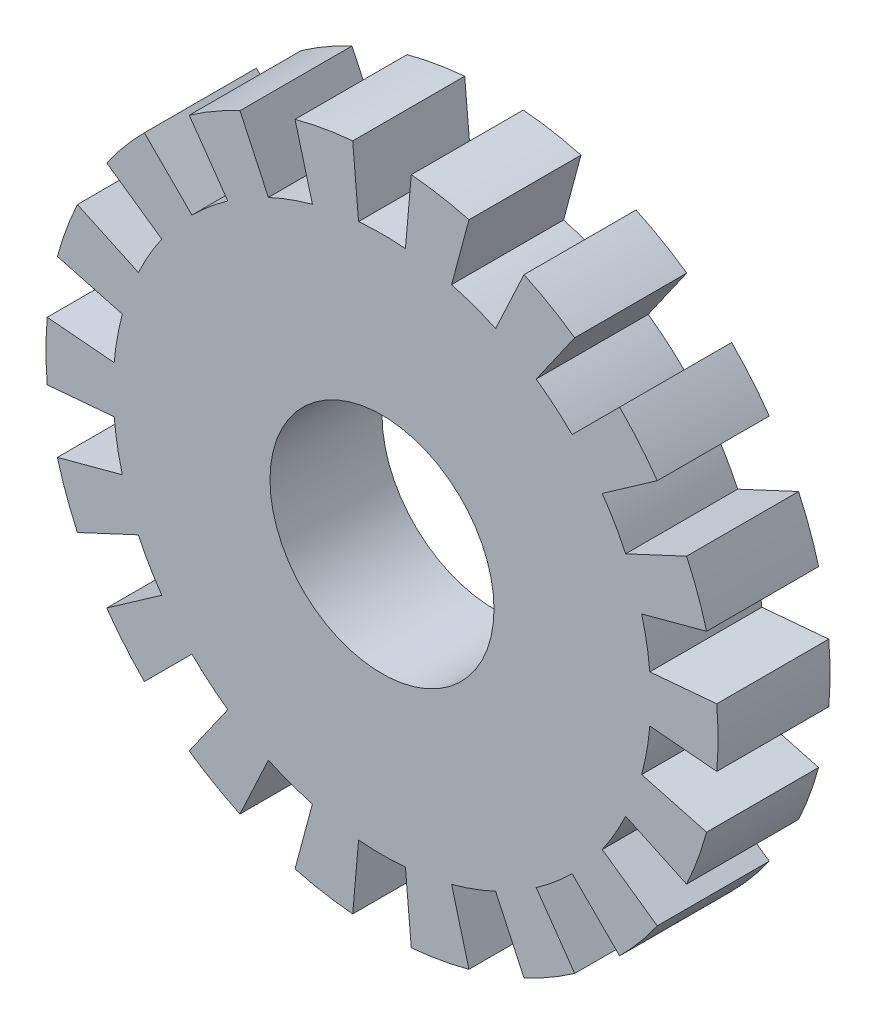
SolidWorks part; units mm, degrees
ref_plane "正面" through (0, 0, 0) normal (0, 0, 1) x (1, 0, 0)
ref_plane "平面" through (0, 0, 0) normal (0, 1, 0) x (1, 0, 0)
ref_plane "右側面" through (0, 0, 0) normal (1, 0, 0) x (0, 0, -1)
sketch "ｽｹｯﾁ1" plane through (0, 0, 0) normal (0, 0, 1) x (1, 0, 0)
  circle A0 centre (0, 0) radius 15
  dimension "D1" = 30
extrude "ﾎﾞｽ - 押し出し1" add sketch "ｽｹｯﾁ1" along normal blind 5
sketch "ｽｹｯﾁ2" plane through (0, 0, 0) normal (0, 0, -1) x (-1, 0, 0)
  line L0 (0, 0) -> (0, 15) construction
  line L1 (0, 0) -> (1.0459, 11.9543) construction
  line L2 (1.0459, 11.9543) -> (1.3073, 14.9429)
  line L3 (0, 12) -> (0, 15)
  line L4 (-1.0459, 11.9543) -> (-1.3073, 14.9429)
  line L5 (5.0714, 10.8757) -> (6.3393, 13.5946)
  line L6 (3.1058, 11.5911) -> (3.8823, 14.4889)
  line L7 (8.4853, 8.4853) -> (10.6066, 10.6066)
  line L8 (6.8829, 9.8298) -> (8.6036, 12.2873)
  line L9 (10.8757, 5.0714) -> (13.5946, 6.3393)
  line L10 (9.8298, 6.8829) -> (12.2873, 8.6036)
  line L11 (11.9543, 1.0459) -> (14.9429, 1.3073)
  line L12 (11.5911, 3.1058) -> (14.4889, 3.8823)
  line L13 (11.5911, -3.1058) -> (14.4889, -3.8823)
  line L14 (11.9543, -1.0459) -> (14.9429, -1.3073)
  line L15 (9.8298, -6.8829) -> (12.2873, -8.6036)
  line L16 (10.8757, -5.0714) -> (13.5946, -6.3393)
  line L17 (6.8829, -9.8298) -> (8.6036, -12.2873)
  line L18 (8.4853, -8.4853) -> (10.6066, -10.6066)
  line L19 (3.1058, -11.5911) -> (3.8823, -14.4889)
  line L20 (5.0714, -10.8757) -> (6.3393, -13.5946)
  line L21 (-1.0459, -11.9543) -> (-1.3073, -14.9429)
  line L22 (1.0459, -11.9543) -> (1.3073, -14.9429)
  line L23 (-5.0714, -10.8757) -> (-6.3393, -13.5946)
  line L24 (-3.1058, -11.5911) -> (-3.8823, -14.4889)
  line L25 (-8.4853, -8.4853) -> (-10.6066, -10.6066)
  line L26 (-6.8829, -9.8298) -> (-8.6036, -12.2873)
  line L27 (-10.8757, -5.0714) -> (-13.5946, -6.3393)
  line L28 (-9.8298, -6.8829) -> (-12.2873, -8.6036)
  line L29 (-11.9543, -1.0459) -> (-14.9429, -1.3073)
  line L30 (-11.5911, -3.1058) -> (-14.4889, -3.8823)
  line L31 (-11.5911, 3.1058) -> (-14.4889, 3.8823)
  line L32 (-11.9543, 1.0459) -> (-14.9429, 1.3073)
  line L33 (-9.8298, 6.8829) -> (-12.2873, 8.6036)
  line L34 (-10.8757, 5.0714) -> (-13.5946, 6.3393)
  line L35 (-6.8829, 9.8298) -> (-8.6036, 12.2873)
  line L36 (-8.4853, 8.4853) -> (-10.6066, 10.6066)
  line L37 (-3.1058, 11.5911) -> (-3.8823, 14.4889)
  line L38 (-5.0714, 10.8757) -> (-6.3393, 13.5946)
  circle A0 centre (0, 0) radius 15 construction
  arc A1 (1.0459, 11.9543) -> (-1.0459, 11.9543) centre (0, 0) ccw
  arc A2 (-1.3073, 14.9429) -> (1.3073, 14.9429) centre (0, 0) cw
  arc A3 (3.8823, 14.4889) -> (6.3393, 13.5946) centre (0, 0) cw
  arc A4 (5.0714, 10.8757) -> (3.1058, 11.5911) centre (0, 0) ccw
  arc A5 (8.6036, 12.2873) -> (10.6066, 10.6066) centre (0, 0) cw
  arc A6 (8.4853, 8.4853) -> (6.8829, 9.8298) centre (0, 0) ccw
  arc A7 (12.2873, 8.6036) -> (13.5946, 6.3393) centre (0, 0) cw
  arc A8 (10.8757, 5.0714) -> (9.8298, 6.8829) centre (0, 0) ccw
  arc A9 (14.4889, 3.8823) -> (14.9429, 1.3073) centre (0, 0) cw
  arc A10 (11.9543, 1.0459) -> (11.5911, 3.1058) centre (0, 0) ccw
  arc A11 (14.9429, -1.3073) -> (14.4889, -3.8823) centre (0, 0) cw
  arc A12 (11.5911, -3.1058) -> (11.9543, -1.0459) centre (0, 0) ccw
  arc A13 (13.5946, -6.3393) -> (12.2873, -8.6036) centre (0, 0) cw
  arc A14 (9.8298, -6.8829) -> (10.8757, -5.0714) centre (0, 0) ccw
  arc A15 (10.6066, -10.6066) -> (8.6036, -12.2873) centre (0, 0) cw
  arc A16 (6.8829, -9.8298) -> (8.4853, -8.4853) centre (0, 0) ccw
  arc A17 (6.3393, -13.5946) -> (3.8823, -14.4889) centre (0, 0) cw
  arc A18 (3.1058, -11.5911) -> (5.0714, -10.8757) centre (0, 0) ccw
  arc A19 (1.3073, -14.9429) -> (-1.3073, -14.9429) centre (0, 0) cw
  arc A20 (-1.0459, -11.9543) -> (1.0459, -11.9543) centre (0, 0) ccw
  arc A21 (-3.8823, -14.4889) -> (-6.3393, -13.5946) centre (0, 0) cw
  arc A22 (-5.0714, -10.8757) -> (-3.1058, -11.5911) centre (0, 0) ccw
  arc A23 (-8.6036, -12.2873) -> (-10.6066, -10.6066) centre (0, 0) cw
  arc A24 (-8.4853, -8.4853) -> (-6.8829, -9.8298) centre (0, 0) ccw
  arc A25 (-12.2873, -8.6036) -> (-13.5946, -6.3393) centre (0, 0) cw
  arc A26 (-10.8757, -5.0714) -> (-9.8298, -6.8829) centre (0, 0) ccw
  arc A27 (-14.4889, -3.8823) -> (-14.9429, -1.3073) centre (0, 0) cw
  arc A28 (-11.9543, -1.0459) -> (-11.5911, -3.1058) centre (0, 0) ccw
  arc A29 (-14.9429, 1.3073) -> (-14.4889, 3.8823) centre (0, 0) cw
  arc A30 (-11.5911, 3.1058) -> (-11.9543, 1.0459) centre (0, 0) ccw
  arc A31 (-13.5946, 6.3393) -> (-12.2873, 8.6036) centre (0, 0) cw
  arc A32 (-9.8298, 6.8829) -> (-10.8757, 5.0714) centre (0, 0) ccw
  arc A33 (-10.6066, 10.6066) -> (-8.6036, 12.2873) centre (0, 0) cw
  arc A34 (-6.8829, 9.8298) -> (-8.4853, 8.4853) centre (0, 0) ccw
  arc A35 (-6.3393, 13.5946) -> (-3.8823, 14.4889) centre (0, 0) cw
  arc A36 (-3.1058, 11.5911) -> (-5.0714, 10.8757) centre (0, 0) ccw
  point P82 (0, 0)
  circle M8 centre (0, 0) radius 15
  dimension "D1" = 5
  dimension "D2" = 18
  dimension "D3" = 3
extrude "ｶｯﾄ - 押し出し1" cut sketch "ｽｹｯﾁ2" against normal up to next contours A34 L35 L36 M8 | A36 L37 L38 M8 | A1 L2 L3 M8 | A1 L3 L4 M8 | A4 L5 L6 M8 | A6 L7 L8 M8 | A8 L9 L10 M8 | A10 L11 L12 M8 | A12 L13 L14 M8 | A32 L33 L34 M8 | A30 L31 L32 M8 | A28 L29 L30 M8 | A26 L27 L28 M8 | A24 L25 L26 M8 | A22 L23 L24 M8 | A20 L21 L22 M8 | A18 L19 L20 M8 | A16 L17 L18 M8 | A14 L15 L16 M8
sketch "ｽｹｯﾁ3" plane through (0, 0, 0) normal (0, 0, -1) x (-1, 0, 0)
  circle A0 centre (0, 0) radius 5
  dimension "D1" = 10
extrude "ｶｯﾄ - 押し出し2" cut sketch "ｽｹｯﾁ3" against normal up to next
